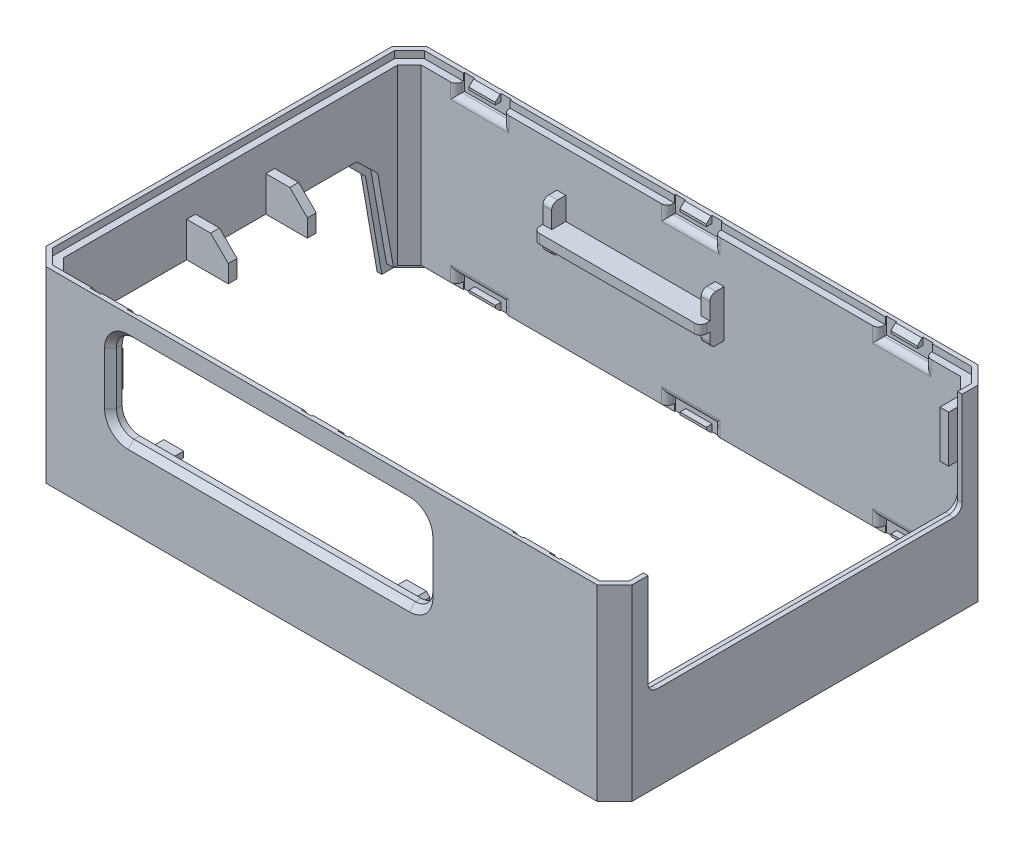
SolidWorks part; units mm, degrees
ref_plane "前视基准面" through (0, 0, 0) normal (0, 0, 1) x (1, 0, 0)
ref_plane "上视基准面" through (0, 0, 0) normal (0, 1, 0) x (1, 0, 0)
ref_plane "右视基准面" through (0, 0, 0) normal (1, 0, 0) x (0, 0, -1)
sketch "草图1" plane through (0, 0, 0) normal (0, 1, 0) x (1, 0, 0)
  line L1 (-50, 32.5) -> (50, 32.5)
  line L2 (-50, 32.5) -> (-50, -32.5)
  line L3 (-50, -32.5) -> (50, -32.5)
  line L4 (50, 32.5) -> (50, -32.5)
  line L5 (-50, 32.5) -> (50, -32.5) construction
  line L6 (-50, -32.5) -> (50, 32.5) construction
  point P0 (0, 0)
  dimension "D1" = 65
  dimension "D2" = 100
extrude "凸台-拉伸1" add sketch "草图1" along normal blind 32
sketch "草图2" plane through (0, 32, 0) normal (0, 1, 0) x (1, 0, 0)
  line L8 (48, -30.5) -> (48, 30.5)
  line L9 (48, 30.5) -> (-48, 30.5)
  line L10 (-48, 30.5) -> (-48, -30.5)
  line L11 (-48, -30.5) -> (48, -30.5)
  line L12 (48, -30.5) -> (48, 30.5)
  line L13 (48, 30.5) -> (-48, 30.5)
  line L14 (-48, 30.5) -> (-48, -30.5)
  line L15 (-48, -30.5) -> (48, -30.5)
  dimension "D1" = 2
extrude "切除-拉伸1" cut sketch "草图2" against normal through all
sketch "草图4" plane through (-50, 0, 0) normal (-1, 0, 0) x (0, 0, 1)
  line L0 (-32.5, 0) -> (32.5, 0) construction
  line L3 (-28, 0) -> (28, 0)
  line L7 (-25.0863, 16.5) -> (-21.5, 20)
  line L8 (21.5, 20) -> (25.09, 16.5)
  line L9 (32.5, 32) -> (32.5, 0) construction
  line L12 (-25.0863, 16.5) -> (-28, 0)
  line L13 (-21.5, 20) -> (21.5, 20)
  line L14 (25.09, 16.5) -> (28, 0)
  line L15 (-32.5, 0) -> (32.5, 0) construction
  line L16 (-32.5, 32) -> (-32.5, 0) construction
  dimension "D1" = 16.5
  dimension "D2" = 20
  dimension "D3" = 4.5
  dimension "D4" = 4.5
  dimension "D5" = 11
  dimension "D6" = 11
  dimension "D7" = 7.4137
  dimension "D8" = 7.41
extrude "切除-拉伸2" cut sketch "草图4" against normal blind 2
sketch "草图7" plane through (0, 0, 32.5) normal (0, 0, 1) x (1, 0, 0)
  line L0 (-50, 32) -> (-50, 0) construction
  line L5 (-50, 32) -> (50, 32) construction
  line L16 (-36, 28) -> (-36, 13)
  line L17 (18, 28) -> (-36, 28)
  line L18 (18, 13) -> (18, 28)
  line L19 (-36, 13) -> (18, 13)
  dimension "D1" = 54
  dimension "D2" = 15
  dimension "D3" = 14
  dimension "D4" = 4
extrude "切除-拉伸3" cut sketch "草图7" against normal blind 2.5
fillet "圆角7" radius 3 4 edges at (-36, 28, 31.5) (18, 28, 31.5) (18, 13, 31.5) (-36, 13, 31.5)
chamfer "倒角1" distance 1 angle 45 8 edges at (-9, 28, 32.5) (-35.1213, 27.1213, 32.5) (17.1213, 27.1213, 32.5) (-36, 20.5, 32.5) (18, 20.5, 32.5) (-35.1213, 13.8787, 32.5) (17.1213, 13.8787, 32.5) (-9, 13, 32.5)
ref_plane "基准面4" through (0, 19.25, 0) normal (0, -1, 0) x (-1, 0, 0)
sketch "草图17" plane through (-48, 0, 0) normal (1, 0, 0) x (0, 0, -1)
  line L1 (-6, 20) -> (-7.5, 20)
  line L2 (-6, 20) -> (-6, 26)
  line L3 (-6, 26) -> (-7.5, 26)
  line L4 (-7.5, 20) -> (-7.5, 26)
  line L5 (32.5, 32) -> (32.5, 0) construction
  line L6 (6, 20) -> (7.5, 20)
  line L7 (6, 20) -> (6, 26)
  line L8 (6, 26) -> (7.5, 26)
  line L9 (7.5, 20) -> (7.5, 26)
  line L10 (-21.5, 20) -> (21.5, 20) construction
  line L12 (-32.5, 32) -> (-32.5, 0) construction
  dimension "D1" = 1.5
  dimension "D2" = 1.5
  dimension "D3" = 25
  dimension "D4" = 25
  dimension "D5" = 6
extrude "凸台-拉伸6" add sketch "草图17" along normal blind 7.1
chamfer "倒角6" distance 3 angle 45 2 edges at (-40.9, 26, -6.75) (-40.9, 26, 6.75)
chamfer "倒角7" distance 2 angle 45 4 edges at (-48, 16, -30.5) (-48, 16, 30.5) (48, 16, -30.5) (48, 16, 30.5)
chamfer "倒角8" distance 3 angle 45 4 edges at (-50, 16, 32.5) (-50, 16, -32.5) (50, 16, -32.5) (50, 16, 32.5)
sketch "草图28" plane through (-50, 0, 0) normal (-1, 0, 0) x (0, 0, 1)
  line L27 (-29.3, 22.3393) -> (-29.3, 0)
  line L28 (-29.3, 0) -> (-26.9872, 0)
  line L29 (-26.9872, 0) -> (-24.2154, 15.8784)
  line L30 (-24.2154, 15.8784) -> (-21.1176, 18.9896)
  line L31 (-21.1176, 18.9896) -> (21.1176, 18.9896)
  line L32 (21.1176, 18.9896) -> (24.2152, 15.8784)
  line L33 (24.2152, 15.8784) -> (27.008, 0)
  line L34 (27.008, 0) -> (29.3, 0)
  line L35 (29.3, 0) -> (29.3, 22.3393)
  line L36 (29.3, 22.3393) -> (-29.3, 22.3393)
  line L37 (28.5, 0) -> (-28.5, 0) construction
  line L38 (-29.5, 0) -> (-28, 0) construction
  line L39 (28, 0) -> (29.5, 0) construction
extrude "凸台-拉伸13" add sketch "草图28" against normal blind 0.8
sketch "草图35" plane through (48, 0, 0) normal (-1, 0, 0) x (0, 0, 1)
  line L0 (-28, 32) -> (28, 32)
  line L1 (-28, 32) -> (-28, 14)
  line L2 (-28, 14) -> (28, 14)
  line L3 (28, 32) -> (28, 14)
  line L4 (32.5, 0) -> (32.5, 32) construction
  line L5 (-32.5, 32) -> (-32.5, 0) construction
  line L6 (28.5, 32) -> (-28.5, 32) construction
  dimension "D1" = 18
  dimension "D3" = 4.5
  dimension "D4" = 4.5
extrude "切除-拉伸6" cut sketch "草图35" against normal blind 1.2
fillet "圆角17" radius 2 2 edges at (48.6, 14, -28) (48.6, 14, 28)
sketch "草图39" plane through (49.2, 0, 0) normal (-1, 0, 0) x (0, 0, 1)
  line L0 (32.5, 0) -> (32.5, 32) construction
  line L1 (-32.5, 32) -> (-32.5, 0) construction
  line L2 (28, 32) -> (-28, 32) construction
  line L3 (29.5, 32) -> (-29.5, 32) construction
  line L4 (29.5, 0) -> (-29.5, 0) construction
  line L12 (-26.8, 32) -> (-26.8, 16)
  line L13 (-25.3, 14.5) -> (25.3, 14.5)
  line L14 (26.8, 16) -> (26.8, 32)
  line L15 (26.8, 32) -> (-26.8, 32)
  arc A6 (-26.8, 16) -> (-25.3, 14.5) centre (-25.3, 16) ccw
  arc A7 (25.3, 14.5) -> (26.8, 16) centre (25.3, 16) ccw
  dimension "D1" = 7.2
  dimension "D2" = 7.2
  dimension "D3" = 16
  dimension "D4" = 14.5
extrude "切除-拉伸7" cut sketch "草图39" against normal blind 1.2
ref_plane "基准面5" through (-50, 32, 29.5) normal (0.7071, 0, 0.7071) x (0.7071, 0, -0.7071)
sketch "草图44" plane through (0, 0, -28) normal (0, 0, 1) x (1, 0, 0)
  line L0 (48, 32) -> (48, 16) construction
  line L1 (48, 28.5) -> (46.5, 28.5)
  line L2 (48, 28.5) -> (48, 20.5)
  line L3 (48, 20.5) -> (46.5, 20.5)
  line L4 (46.5, 28.5) -> (46.5, 20.5)
  line L5 (50, 14.5) -> (49.2, 14.5) construction
  dimension "D1" = 1.5
  dimension "D2" = 8
  dimension "D3" = 6
extrude "凸台-拉伸15" add sketch "草图44" along normal blind 1.5 and the other way up to surface other way up to face at (0, 16, -30.5)
sketch "草图45" plane through (0, 0, 28) normal (0, 0, -1) x (-1, 0, 0)
  line L4 (-48, 28.5) -> (-48, 20.5)
  line L5 (-46.5, 28.5) -> (-48, 28.5)
  line L6 (-46.5, 20.5) -> (-46.5, 28.5)
  line L7 (-48, 20.5) -> (-46.5, 20.5)
  line L8 (-48, 28.5) -> (-48, 20.5)
  line L9 (-46.5, 28.5) -> (-48, 28.5)
  line L10 (-46.5, 20.5) -> (-46.5, 28.5)
  line L11 (-48, 20.5) -> (-46.5, 20.5)
  dimension "D1" = 0
extrude "凸台-拉伸16" add sketch "草图45" along normal blind 1.5 and the other way up to surface
ref_plane "基准面6" through (48, 0, -28.5) normal (0, 0, -1) x (-1, 0, 0)
sketch "草图48" plane through (0, 32, 0) normal (0, 1, 0) x (1, 0, 0)
  line L31 (49.2, 29.1686) -> (49.2, -29.1686)
  line L32 (46.6686, -31.7) -> (49.2, -29.1686)
  line L33 (-46.6686, -31.7) -> (46.6686, -31.7)
  line L34 (-49.2, -29.1686) -> (-46.6686, -31.7)
  line L35 (-49.2, 29.1686) -> (-49.2, -29.1686)
  line L36 (-46.6686, 31.7) -> (-49.2, 29.1686)
  line L37 (46.6686, 31.7) -> (-46.6686, 31.7)
  line L38 (49.2, 29.1686) -> (46.6686, 31.7)
  point P0 (48, 30.5)
  point P1 (-48, -30.5)
  point P2 (48, -30.5)
  point P3 (-48, 30.5)
extrude "切除-拉伸8" cut sketch "草图48" against normal blind 1.2
sketch "草图57" plane through (0, 0, 30.5) normal (0, 0, -1) x (-1, 0, 0)
  line L1 (-21.2, 16) -> (-22.7, 16)
  line L2 (-21.2, 16) -> (-21.2, 22)
  line L3 (-21.2, 22) -> (-22.7, 22)
  line L4 (-22.7, 16) -> (-22.7, 22)
  line L5 (39.4, 16) -> (40.9, 16)
  line L6 (39.4, 16) -> (39.4, 22)
  line L7 (39.4, 22) -> (40.9, 22)
  line L8 (40.9, 16) -> (40.9, 22)
  line L9 (47, 32) -> (-47, 32) construction
  line L10 (-50, 32) -> (-50, 0) construction
  line L11 (50, 0) -> (50, 32) construction
  line L12 (46, 0) -> (-46, 0) construction
  line L17 (-14, 12) -> (-10, 12)
  line L18 (-14, 12) -> (-14, 11)
  line L19 (-14, 11) -> (-10, 11)
  line L20 (-10, 12) -> (-10, 11)
  line L21 (28, 12) -> (32, 12)
  line L22 (28, 12) -> (28, 11)
  line L23 (28, 11) -> (32, 11)
  line L24 (32, 12) -> (32, 11)
  dimension "D1" = 1.5
  dimension "D2" = 16
  dimension "D3" = 28.8
  dimension "D4" = 10.6
  dimension "D5" = 4
  dimension "D6" = 4
  dimension "D7" = 1
  dimension "D8" = 1
  dimension "D9" = 12
  dimension "D10" = 18
  dimension "D11" = 60
  dimension "D12" = 6
extrude "凸台-拉伸27" add sketch "草图57" along normal blind 2.5
sketch "草图60" plane through (21.2, 0, 0) normal (-1, 0, 0) x (0, 0, 1)
  line L0 (28, 22) -> (30.5, 22) construction
  line L1 (28, 22) -> (29.25, 22)
  line L2 (28, 22) -> (28, 16)
  line L3 (28, 16) -> (29.25, 16)
  line L4 (29.25, 22) -> (29.25, 16)
  line L5 (28, 16) -> (30.5, 16) construction
  dimension "D1" = 1.25
extrude "凸台-拉伸28" add sketch "草图60" along normal blind 1
sketch "草图61" plane through (-39.4, 0, 0) normal (1, 0, 0) x (0, 0, -1)
  line L4 (-28, 16) -> (-28, 22)
  line L5 (-29.25, 16) -> (-28, 16)
  line L6 (-29.25, 22) -> (-29.25, 16)
  line L7 (-28, 22) -> (-29.25, 22)
  line L8 (-28, 16) -> (-28, 22)
  line L9 (-29.25, 16) -> (-28, 16)
  line L10 (-29.25, 22) -> (-29.25, 16)
  line L11 (-28, 22) -> (-29.25, 22)
  dimension "D1" = 0
extrude "凸台-拉伸29" add sketch "草图61" along normal blind 1
chamfer "倒角16" distance 0.6 angle 45 2 edges at (14, 12, 29.25) (-32, 12, 29.25)
sketch "草图62" plane through (0, 0, 0) normal (0, -1, 0) x (1, 0, 0)
  line L15 (-49.2, 28.9971) -> (-49.2, -28.9971)
  line L16 (-46.4971, -31.7) -> (-49.2, -28.9971)
  line L17 (46.4971, -31.7) -> (-46.4971, -31.7)
  line L18 (49.2, -28.9971) -> (46.4971, -31.7)
  line L19 (49.2, 28.9971) -> (49.2, -28.9971)
  line L20 (46.4971, 31.7) -> (49.2, 28.9971)
  line L21 (-46.4971, 31.7) -> (46.4971, 31.7)
  line L22 (-49.2, 28.9971) -> (-46.4971, 31.7)
extrude "切除-拉伸9" cut sketch "草图62" against normal blind 1.2 contours L15 L16 L17 L18 L19 L20 L21 L22
sketch "草图63" plane through (0, 0, -30.5) normal (0, 0, 1) x (1, 0, 0)
  line L1 (-22.8279, 18.4) -> (5.6721, 18.4)
  line L2 (-22.8279, 18.4) -> (-22.8279, 20)
  line L3 (-22.8279, 20) -> (5.6721, 20)
  line L4 (5.6721, 18.4) -> (5.6721, 20)
extrude "凸台-拉伸30" add sketch "草图63" along normal blind 4
sketch "草图64" plane through (0, 0, -30.5) normal (0, 0, 1) x (1, 0, 0)
  line L1 (-22.8279, 15.8832) -> (-21.3279, 15.8832)
  line L2 (-22.8279, 15.8832) -> (-22.8279, 23.8832)
  line L3 (-22.8279, 23.8832) -> (-21.3279, 23.8832)
  line L4 (-21.3279, 15.8832) -> (-21.3279, 23.8832)
  line L5 (4.1721, 15.8832) -> (5.6721, 15.8832)
  line L6 (4.1721, 15.8832) -> (4.1721, 23.8832)
  line L7 (4.1721, 23.8832) -> (5.6721, 23.8832)
  line L8 (5.6721, 15.8832) -> (5.6721, 23.8832)
extrude "凸台-拉伸31" add sketch "草图64" along normal blind 2.4
fillet "圆角18" radius 1 6 edges at (-22.8279, 19.2, -26.5) (5.6721, 19.2, -26.5) (4.9221, 15.8832, -28.1) (-22.0779, 15.8832, -28.1) (4.9221, 23.8832, -28.1) (-22.0779, 23.8832, -28.1)
sketch "草图65" plane through (0, 0, -30.5) normal (0, 0, 1) x (1, 0, 0)
  line L0 (-47, 32) -> (47, 32) construction
  line L1 (32, 32) -> (40, 32)
  line L2 (32, 32) -> (32, 29.2)
  line L3 (32, 29.2) -> (40, 29.2)
  line L4 (40, 32) -> (40, 29.2)
  line L5 (50, 32) -> (50, 0) construction
  line L7 (-4, 32) -> (4, 32)
  line L8 (-4, 32) -> (-4, 29.2)
  line L9 (-4, 29.2) -> (4, 29.2)
  line L10 (4, 32) -> (4, 29.2)
  line L12 (-40, 32) -> (-32, 32)
  line L13 (-40, 32) -> (-40, 29.2)
  line L14 (-40, 29.2) -> (-32, 29.2)
  line L15 (-32, 32) -> (-32, 29.2)
  line L16 (-40, 0) -> (-32, 0)
  line L17 (-40, 0) -> (-40, 2.8)
  line L18 (-40, 2.8) -> (-32, 2.8)
  line L19 (-32, 0) -> (-32, 2.8)
  line L20 (-4, 0) -> (4, 0)
  line L21 (-4, 0) -> (-4, 2.8)
  line L22 (-4, 2.8) -> (4, 2.8)
  line L23 (4, 0) -> (4, 2.8)
  line L24 (32, 0) -> (40, 0)
  line L25 (32, 0) -> (32, 2.8)
  line L26 (32, 2.8) -> (40, 2.8)
  line L27 (40, 0) -> (40, 2.8)
  dimension "D1" = 2.8
  dimension "D2" = 10
  dimension "D3" = 8
  dimension "D6" = 28
  dimension "D7" = 28
extrude "切除-拉伸10" cut sketch "草图65" against normal blind 1.4
sketch "草图67" plane through (0, 0, 30.5) normal (0, 0, -1) x (-1, 0, 0)
  line L4 (4, 32) -> (-4, 32)
  line L5 (-4, 32) -> (-4, 29.2)
  line L6 (-4, 29.2) -> (4, 29.2)
  line L7 (4, 29.2) -> (4, 32)
  line L8 (4, 32) -> (-4, 32)
  line L9 (-4, 32) -> (-4, 29.2)
  line L10 (-4, 29.2) -> (4, 29.2)
  line L11 (4, 29.2) -> (4, 32)
  line L12 (-32, 32) -> (-40, 32)
  line L13 (-40, 32) -> (-40, 29.2)
  line L14 (-40, 29.2) -> (-32, 29.2)
  line L15 (-32, 29.2) -> (-32, 32)
  line L16 (-32, 32) -> (-40, 32)
  line L17 (-40, 32) -> (-40, 29.2)
  line L18 (-40, 29.2) -> (-32, 29.2)
  line L19 (-32, 29.2) -> (-32, 32)
  line L20 (-40, 0) -> (-32, 0)
  line L21 (-40, 2.8) -> (-40, 0)
  line L22 (-32, 2.8) -> (-40, 2.8)
  line L23 (-32, 0) -> (-32, 2.8)
  line L24 (-40, 0) -> (-32, 0)
  line L25 (-40, 2.8) -> (-40, 0)
  line L26 (-32, 2.8) -> (-40, 2.8)
  line L27 (-32, 0) -> (-32, 2.8)
  line L28 (-4, 0) -> (4, 0)
  line L29 (-4, 2.8) -> (-4, 0)
  line L30 (4, 2.8) -> (-4, 2.8)
  line L31 (4, 0) -> (4, 2.8)
  line L32 (-4, 0) -> (4, 0)
  line L33 (-4, 2.8) -> (-4, 0)
  line L34 (4, 2.8) -> (-4, 2.8)
  line L35 (4, 0) -> (4, 2.8)
  line L36 (32, 0) -> (40, 0)
  line L37 (40, 0) -> (40, 2.8)
  line L38 (40, 2.8) -> (32, 2.8)
  line L39 (32, 2.8) -> (32, 0)
  line L40 (32, 0) -> (40, 0)
  line L41 (40, 0) -> (40, 2.8)
  line L42 (40, 2.8) -> (32, 2.8)
  line L43 (32, 2.8) -> (32, 0)
  line L44 (40, 32) -> (32, 32)
  line L45 (40, 29.2) -> (40, 32)
  line L46 (32, 29.2) -> (40, 29.2)
  line L47 (32, 32) -> (32, 29.2)
  line L48 (40, 32) -> (32, 32)
  line L49 (40, 29.2) -> (40, 32)
  line L50 (32, 29.2) -> (40, 29.2)
  line L51 (32, 32) -> (32, 29.2)
  dimension "D1" = 0
  dimension "D2" = 0
  dimension "D3" = 0
  dimension "D4" = 0
  dimension "D5" = 0
  dimension "D6" = 0
extrude "切除-拉伸11" cut sketch "草图67" against normal blind 1.4
fillet "圆角19" radius 1 36 edges at (-32, 30, -30.5) (-36, 29.2, -30.5) (-40, 30, -30.5) (40, 30, -30.5) (36, 29.2, -30.5) (32, 30, -30.5) (4, 30, -30.5) (0, 29.2, -30.5) (-4, 30, -30.5) (-40, 30, 30.5) (-36, 29.2, 30.5) (-32, 30, 30.5) (-4, 30, 30.5) (0, 29.2, 30.5) (4, 30, 30.5) (32, 30, 30.5) (40, 30, 30.5) (36, 29.2, 30.5) (4, 2, 30.5) (-4, 2, 30.5) (0, 2.8, 30.5) (40, 2, 30.5) (32, 2, 30.5) (36, 2.8, 30.5) (-36, 2.8, 30.5) (-32, 2, 30.5) (-40, 2, 30.5) (40, 2, -30.5) (32, 2, -30.5) (36, 2.8, -30.5) (-4, 2, -30.5) (4, 2, -30.5) (0, 2.8, -30.5) (-36, 2.8, -30.5) (-32, 2, -30.5) (-40, 2, -30.5)
sketch "草图70" plane through (0, 0, -31.9) normal (0, 0, 1) x (1, 0, 0)
  line L0 (-32, 32) -> (-40, 32) construction
  line L1 (-38.25, 32) -> (-33.75, 32)
  line L2 (-38.25, 32) -> (-38.25, 30.8)
  line L3 (-38.25, 30.8) -> (-33.75, 30.8)
  line L4 (-33.75, 32) -> (-33.75, 30.8)
  line L5 (-38.25, 32) -> (-33.75, 30.8) construction
  line L6 (-38.25, 30.8) -> (-33.75, 32) construction
  line L7 (-2.25, 32) -> (2.25, 32)
  line L8 (-2.25, 32) -> (-2.25, 30.8)
  line L9 (-2.25, 30.8) -> (2.25, 30.8)
  line L10 (2.25, 32) -> (2.25, 30.8)
  line L11 (-2.25, 32) -> (2.25, 30.8) construction
  line L12 (-2.25, 30.8) -> (2.25, 32) construction
  line L13 (33.75, 32) -> (38.25, 32)
  line L14 (33.75, 32) -> (33.75, 30.8)
  line L15 (33.75, 30.8) -> (38.25, 30.8)
  line L16 (38.25, 32) -> (38.25, 30.8)
  line L17 (33.75, 32) -> (38.25, 30.8) construction
  line L18 (33.75, 30.8) -> (38.25, 32) construction
  line L19 (4, 32) -> (-4, 32) construction
  line L20 (40, 32) -> (32, 32) construction
  line L21 (47, 32) -> (-47, 32) construction
  line L22 (-40, 0) -> (-32, 0) construction
  line L23 (33.75, 1.2) -> (38.25, 1.2)
  line L24 (33.75, 1.2) -> (33.75, 0)
  line L25 (33.75, 0) -> (38.25, 0)
  line L26 (38.25, 1.2) -> (38.25, 0)
  line L27 (33.75, 1.2) -> (38.25, 0) construction
  line L28 (33.75, 0) -> (38.25, 1.2) construction
  line L29 (-2.25, 1.2) -> (2.25, 1.2)
  line L30 (-2.25, 1.2) -> (-2.25, 0)
  line L31 (-2.25, 0) -> (2.25, 0)
  line L32 (2.25, 1.2) -> (2.25, 0)
  line L33 (-2.25, 1.2) -> (2.25, 0) construction
  line L34 (-2.25, 0) -> (2.25, 1.2) construction
  line L35 (-38.25, 1.2) -> (-33.75, 1.2)
  line L36 (-38.25, 1.2) -> (-38.25, 0)
  line L37 (-38.25, 0) -> (-33.75, 0)
  line L38 (-33.75, 1.2) -> (-33.75, 0)
  line L39 (-38.25, 1.2) -> (-33.75, 0) construction
  line L40 (-38.25, 0) -> (-33.75, 1.2) construction
  point P0 (-36, 31.4)
  point P5 (0, 31.4)
  point P10 (36, 31.4)
  point P15 (0, 0.6)
  point P18 (-36, 32)
  point P22 (0, 32)
  point P26 (36, 32)
  point P29 (-36, 0.6)
  point P35 (36, 0.6)
  dimension "D1" = 4.5
  dimension "D2" = 1.2
  dimension "D3" = 0
  dimension "D4" = 0
extrude "凸台-拉伸32" add sketch "草图70" along normal blind 1
sketch "草图71" plane through (0, 0, 31.9) normal (0, 0, -1) x (-1, 0, 0)
  line L0 (-38.25, 0) -> (-38.25, 1.2) construction
  line L1 (-38.25, 1.2) -> (-33.75, 1.2) construction
  line L2 (-33.75, 1.2) -> (-33.75, 0) construction
  line L3 (-33.75, 0) -> (-38.25, 0) construction
  line L4 (-2.25, 0) -> (-2.25, 1.2) construction
  line L5 (-2.25, 1.2) -> (2.25, 1.2) construction
  line L6 (2.25, 1.2) -> (2.25, 0) construction
  line L7 (2.25, 0) -> (-2.25, 0) construction
  line L8 (33.75, 0) -> (33.75, 1.2) construction
  line L9 (33.75, 1.2) -> (38.25, 1.2) construction
  line L10 (38.25, 1.2) -> (38.25, 0) construction
  line L11 (38.25, 0) -> (33.75, 0) construction
  line L12 (33.75, 30.8) -> (33.75, 32) construction
  line L13 (33.75, 32) -> (38.25, 32) construction
  line L14 (38.25, 32) -> (38.25, 30.8) construction
  line L15 (38.25, 30.8) -> (33.75, 30.8) construction
  line L16 (-2.25, 30.8) -> (-2.25, 32) construction
  line L17 (-2.25, 32) -> (2.25, 32) construction
  line L18 (2.25, 32) -> (2.25, 30.8) construction
  line L19 (2.25, 30.8) -> (-2.25, 30.8) construction
  line L20 (-38.25, 30.8) -> (-38.25, 32) construction
  line L21 (-38.25, 32) -> (-33.75, 32) construction
  line L22 (-33.75, 32) -> (-33.75, 30.8) construction
  line L23 (-33.75, 30.8) -> (-38.25, 30.8) construction
  line L24 (-38.25, 0) -> (-38.25, 1.2)
  line L25 (-38.25, 1.2) -> (-33.75, 1.2)
  line L26 (-33.75, 1.2) -> (-33.75, 0)
  line L27 (-33.75, 0) -> (-38.25, 0)
  line L28 (-2.25, 0) -> (-2.25, 1.2)
  line L29 (-2.25, 1.2) -> (2.25, 1.2)
  line L30 (2.25, 1.2) -> (2.25, 0)
  line L31 (2.25, 0) -> (-2.25, 0)
  line L32 (33.75, 0) -> (33.75, 1.2)
  line L33 (33.75, 1.2) -> (38.25, 1.2)
  line L34 (38.25, 1.2) -> (38.25, 0)
  line L35 (38.25, 0) -> (33.75, 0)
  line L36 (33.75, 30.8) -> (33.75, 32)
  line L37 (33.75, 32) -> (38.25, 32)
  line L38 (38.25, 32) -> (38.25, 30.8)
  line L39 (38.25, 30.8) -> (33.75, 30.8)
  line L40 (-2.25, 30.8) -> (-2.25, 32)
  line L41 (-2.25, 32) -> (2.25, 32)
  line L42 (2.25, 32) -> (2.25, 30.8)
  line L43 (2.25, 30.8) -> (-2.25, 30.8)
  line L44 (-38.25, 30.8) -> (-38.25, 32)
  line L45 (-38.25, 32) -> (-33.75, 32)
  line L46 (-33.75, 32) -> (-33.75, 30.8)
  line L47 (-33.75, 30.8) -> (-38.25, 30.8)
extrude "凸台-拉伸33" add sketch "草图71" along normal blind 1
chamfer "倒角17" distance 0.8 angle 45 12 edges at (36, 0, -30.9) (0, 0, -30.9) (-36, 0, -30.9) (36, 0, 30.9) (0, 0, 30.9) (-36, 0, 30.9) (-36, 32, 30.9) (0, 32, 30.9) (36, 32, 30.9) (-36, 32, -30.9) (0, 32, -30.9) (36, 32, -30.9)
